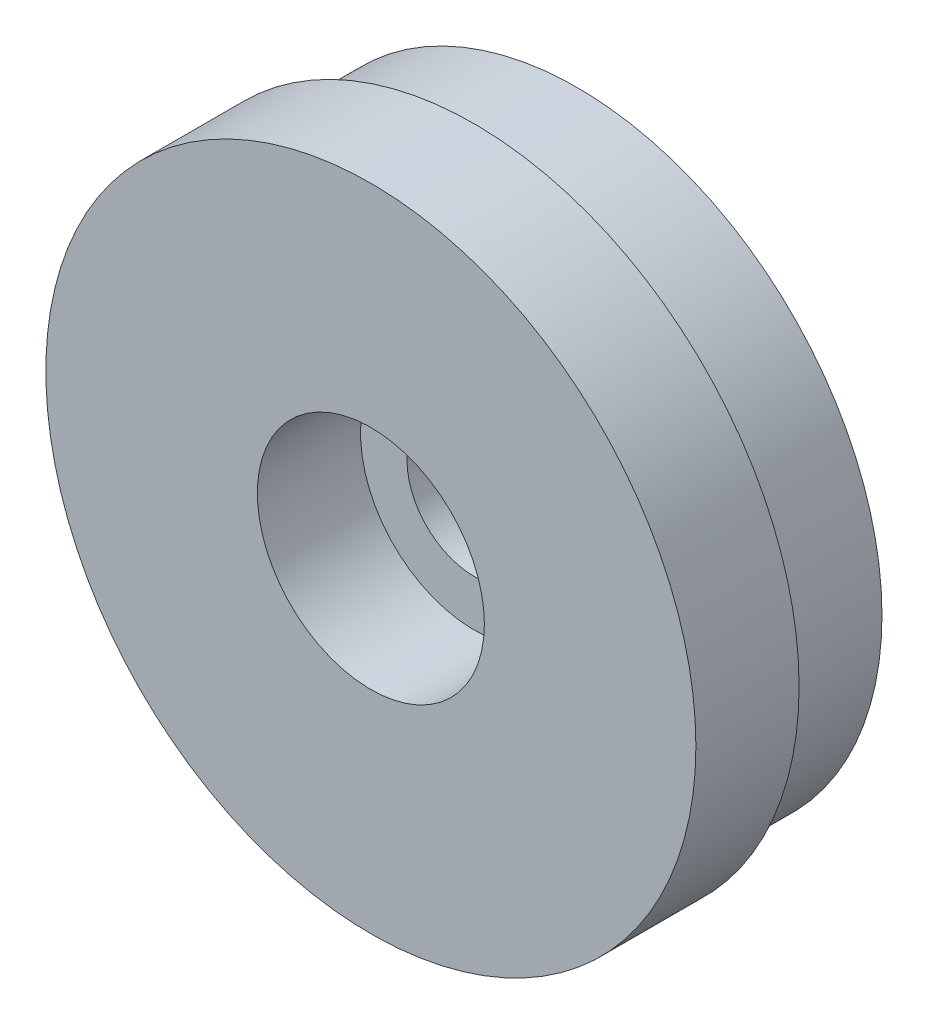
SolidWorks part; units mm, degrees
ref_plane "Front Plane" through (0, 0, 0) normal (0, 0, 1) x (1, 0, 0)
ref_plane "Top Plane" through (0, 0, 0) normal (0, 1, 0) x (1, 0, 0)
ref_plane "Right Plane" through (0, 0, 0) normal (1, 0, 0) x (0, 0, -1)
sketch "Sketch1" plane through (0, 0, 0) normal (0, 0, 1) x (1, 0, 0)
  circle A0 centre (0, 0) radius 8
  circle A1 centre (0, 0) radius 2.794
  point P5 (-0.094, 0)
  dimension "D2" = 5.588
  dimension "D3" = 16
extrude "Boss-Extrude1" add sketch "Sketch1" against normal blind 2.54
sketch "Sketch2" plane through (0, 0, -2.54) normal (0, 0, -1) x (-1, 0, 0)
  circle A0 centre (0, 0) radius 7.5
  circle A1 centre (0, 0) radius 1.651
  point P6 (-0.098, 0)
  dimension "D1" = 15
  dimension "D2" = 3.302
extrude "Boss-Extrude2" add sketch "Sketch2" along normal blind 2.54
